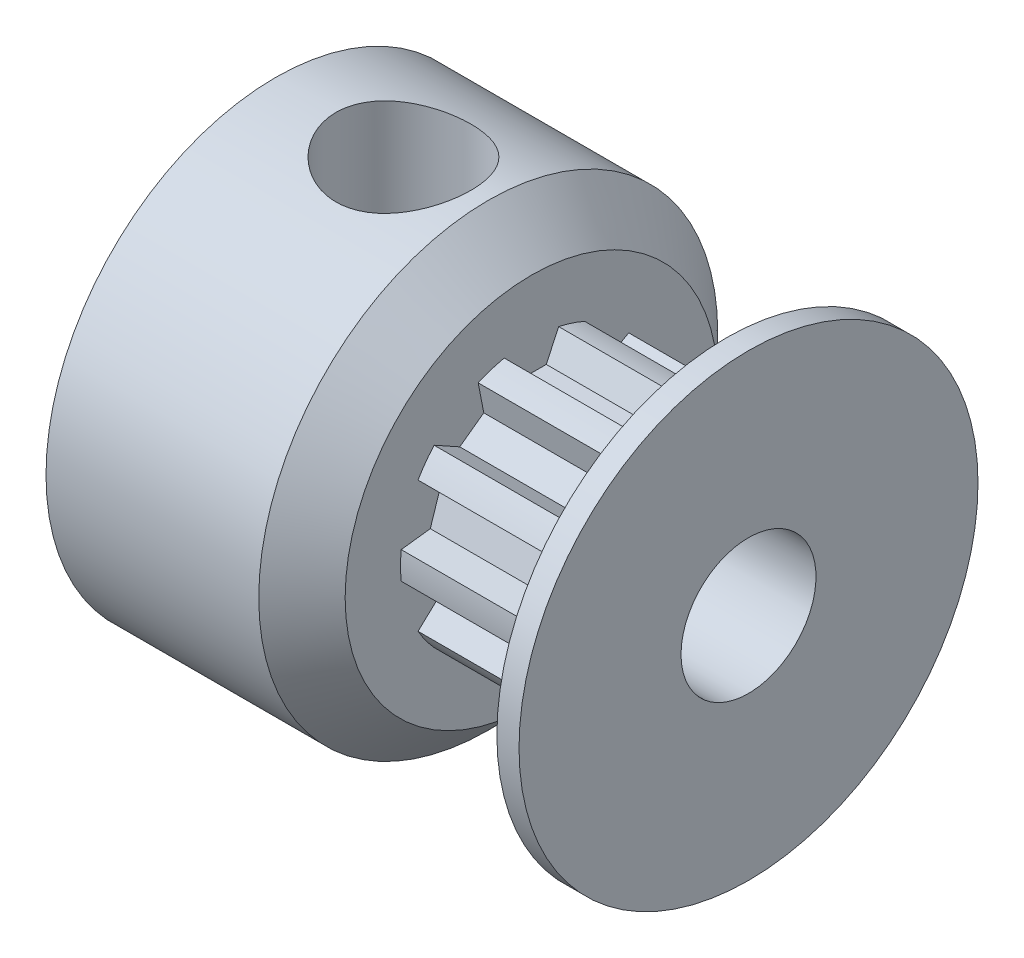
SolidWorks part; units mm, degrees
ref_plane "Front Plane" through (0, 0, 0) normal (0, 0, 1) x (1, 0, 0)
ref_plane "Top Plane" through (0, 0, 0) normal (0, 1, 0) x (1, 0, 0)
ref_plane "Right Plane" through (0, 0, 0) normal (1, 0, 0) x (0, 0, -1)
sketch "Sketch2" plane through (0, 0, 0) normal (1, 0, 0) x (0, 0, -1)
  line L3 (0, 0) -> (0, 2.413) construction
  line L6 (0, -2.921) -> (0, -3.2385) construction
  line L7 (-0.5715, 2.8645) -> (-0.3491, 2.3876)
  line L8 (0.5715, 2.8645) -> (0.3491, 2.3876)
  line L9 (-0.5715, 2.8645) -> (-0.6405, 3.0124)
  line L10 (0.5715, 2.8645) -> (0.6405, 3.0124)
  line L12 (-0.3491, 2.3876) -> (0.3491, 2.3876)
  line L14 (0, 2.921) -> (0, 3.2385) construction
  line L15 (0, 0) -> (0, -1.143) construction
  circle A0 centre (0, 0) radius 3.2385 construction
  circle A1 centre (0, 0) radius 2.413 construction
  circle A2 centre (0, 0) radius 2.921 construction
  arc A7 (0.6405, 3.0124) -> (-0.6405, 3.0124) centre (0, 0) ccw
  point P5 (0, 3.0798)
  dimension "D3" = 0.3175
  dimension "D1" = 50
sketch "Sketch1" plane through (0, 0, 0) normal (0, 0, 1) x (1, 0, 0)
  line L0 (-5.5626, 0) -> (5.5626, 0) construction
  line L1 (-5.5626, 1.5875) -> (5.5626, 1.5875)
  line L2 (-5.5626, 1.5875) -> (-5.5626, 5.3975)
  line L3 (-5.5626, 5.3975) -> (-0.5588, 5.3975)
  line L4 (-0.5588, 5.3975) -> (0.4572, 4.3815)
  line L5 (0.4572, 4.3815) -> (0.4572, 3.2385)
  line L6 (0.4572, 3.2385) -> (4.5212, 3.2385)
  line L7 (4.5212, 3.2385) -> (4.5212, 3.81)
  line L8 (4.5212, 3.2385) -> (5.5626, 3.2385) construction
  line L9 (5.0419, 5.3975) -> (5.5626, 5.3975)
  line L10 (5.5626, 5.3975) -> (5.5626, 1.5875)
  line L11 (5.0419, 3.2385) -> (5.0419, 5.3975) construction
  line L12 (-3.0607, 5.3975) -> (-3.0607, 1.5875) construction
  arc A0 (4.5212, 3.81) -> (5.0419, 5.3975) centre (7.2015, 3.81) cw
  dimension "Bore Size" = 3.175
  dimension "Overall Width" = 11.1252
  dimension "Inside Width" = 4.064
  dimension "Outside Width" = 5.1054
  dimension "Hub Dia" = 10.795
  dimension "OD" = 10.795
  dimension "D1" = 45
  dimension "D2" = 6.477
  dimension "D3" = 1.143
  dimension "D4" = 0.5715
revolve "Revolve1" add sketch "Sketch1" angle 360 mid plane about L0
sketch "Sketch4" plane through (0.4572, 0, 0) normal (1, 0, 0) x (0, 0, -1)
  circle A0 centre (0, 0) radius 3.0798
  circle A1 centre (0, 0) radius 3.2385 construction
  circle A2 centre (0, 0) radius 3.2385
extrude "Cut-Extrude2" cut sketch "Sketch4" along normal up to surface (4.064 mm away) up to face at (4.5212, 0, 3.2385)
sketch "Sketch3" plane through (0.4572, 0, 0) normal (1, 0, 0) x (0, 0, -1)
  line L2 (-0.5715, 2.8645) -> (-0.3491, 2.3876) construction
  line L3 (-0.3491, 2.3876) -> (0.3491, 2.3876) construction
  line L4 (0.5715, 2.8645) -> (0.3491, 2.3876) construction
  line L5 (-0.6405, 3.0124) -> (-0.3491, 2.3876)
  line L6 (-0.3491, 2.3876) -> (0.3491, 2.3876)
  line L7 (0.6405, 3.0124) -> (0.3491, 2.3876)
  arc A1 (0.6405, 3.0124) -> (-0.6405, 3.0124) centre (0, 0) ccw construction
  arc A2 (0.6405, 3.0124) -> (-0.6405, 3.0124) centre (0, 0) ccw
extrude "Cut-Extrude1" cut sketch "Sketch3" along normal up to surface (4.064 mm away) up to face at (4.5212, 0, 3.81)
pattern_circular "CirPattern1" count 10 over 360 about axis through (0, 0, 0) along (1, 0, 0) of "Cut-Extrude1"
sketch "Sketch5" plane through (0, 0, 0) normal (0, 0, 1) x (1, 0, 0)
  line L1 (4.5212, 3.81) -> (4.5212, -3.81) construction
  point P0 (4.5212, 0)
sketch "Sketch6" plane through (0, 0, 0) normal (0, 1, 0) x (1, 0, 0)
  line L0 (-5.5626, 0) -> (-4.1402, 0) construction
  line L1 (-5.5626, 5.3975) -> (-5.5626, -5.3975) construction
  line L2 (0.4572, 0) -> (-0.9652, 0) construction
  line L3 (0.4572, -0.3491) -> (0.4572, 0.3491) construction
  circle A0 centre (-2.5527, 0) radius 1.5875
  dimension "D1" = 3.175
extrude "Cut-Extrude3" cut sketch "Sketch6" along normal through all
pattern_circular "CirPattern2" [suppressed] count 2 over 90
equation "\"D3@Sketch2\" = (\"hs@Sketch2\"-\"ht@Sketch2\")/2"
equation "\"D2@Sketch1\" = \"PD@Sketch2\""
equation "\"D3@Sketch1\" = \"hs@Sketch2\""
equation "\"D4@Sketch1\" = \"D3@Sketch1\"/2"
